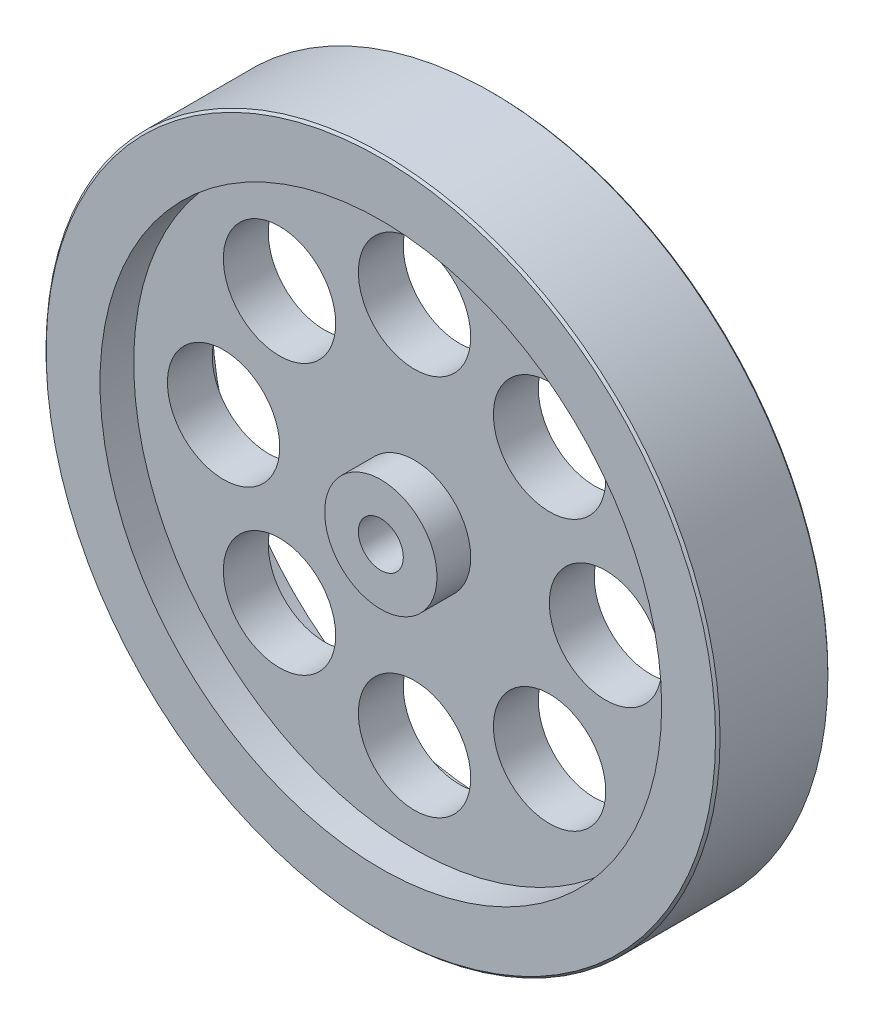
SolidWorks part; units mm, degrees
ref_plane "Front Plane" through (0, 0, 0) normal (0, 0, 1) x (1, 0, 0)
ref_plane "Top Plane" through (0, 0, 0) normal (0, 1, 0) x (1, 0, 0)
ref_plane "Right Plane" through (0, 0, 0) normal (1, 0, 0) x (0, 0, -1)
sketch "Sketch1" plane through (0, 0, 0) normal (0, 0, 1) x (1, 0, 0)
  circle A0 centre (0, 0) radius 30
  dimension "D1" = 60
extrude "Boss-Extrude1" add sketch "Sketch1" along normal mid plane 10
sketch "Sketch2" plane through (0, 0, 5) normal (0, 0, 1) x (1, 0, 0)
  circle A0 centre (0, 0) radius 25
  dimension "D1" = 50
extrude "Cut-Extrude1" cut sketch "Sketch2" against normal blind 3
mirror "Mirror1" about plane through (0, 0, 0) normal (0, 0, 1) of "Cut-Extrude1"
sketch "Sketch3" plane through (0, 0, 2) normal (0, 0, 1) x (1, 0, 0)
  circle A0 centre (0, 17) radius 5
  circle A1 centre (12.0208, 12.0208) radius 5
  circle A2 centre (17, 0) radius 5
  circle A3 centre (12.0208, -12.0208) radius 5
  circle A4 centre (0, -17) radius 5
  circle A5 centre (-12.0208, -12.0208) radius 5
  circle A6 centre (-17, 0) radius 5
  circle A7 centre (-12.0208, 12.0208) radius 5
  point P19 (0, 0)
  dimension "D1" = 10
  dimension "D2" = 17
  dimension "D3" = 8
extrude "Cut-Extrude2" cut sketch "Sketch3" against normal through all both and the other way through all
sketch "Sketch4" plane through (0, 0, 2) normal (0, 0, 1) x (1, 0, 0)
  circle A0 centre (0, 0) radius 5
  dimension "D1" = 10
extrude "Boss-Extrude2" add sketch "Sketch4" along normal blind 3
mirror "Mirror2" about plane through (0, 0, 0) normal (0, 0, 1) of "Boss-Extrude2"
sketch "Sketch5" plane through (0, 0, 0) normal (1, 0, 0) x (0, 0, -1)
  line L0 (-5, 0) -> (5, 0)
  line L1 (-5, 30) -> (-5, -30) construction
  line L2 (5, -30) -> (5, 30) construction
  line L3 (5, 0) -> (5, 3)
  line L4 (5, -5) -> (5, 5) construction
  line L5 (5, 3) -> (3.5, 1.5)
  line L6 (3.5, 1.5) -> (1, 1.5)
  line L7 (1, 1.5) -> (1, 2)
  line L8 (1, 2) -> (-5, 2)
  line L9 (-5, 2) -> (-5, 0)
  dimension "D1" = 1.5
  dimension "D2" = 2.5
  dimension "D3" = 6
  dimension "D4" = 2
  dimension "D5" = 45
revolve "Cut-Revolve1" cut sketch "Sketch5" angle 360 about L0
chamfer "Chamfer1" distance 0.2 angle 45 2 edges at (30, 0, 5) (30, 0, -5)
